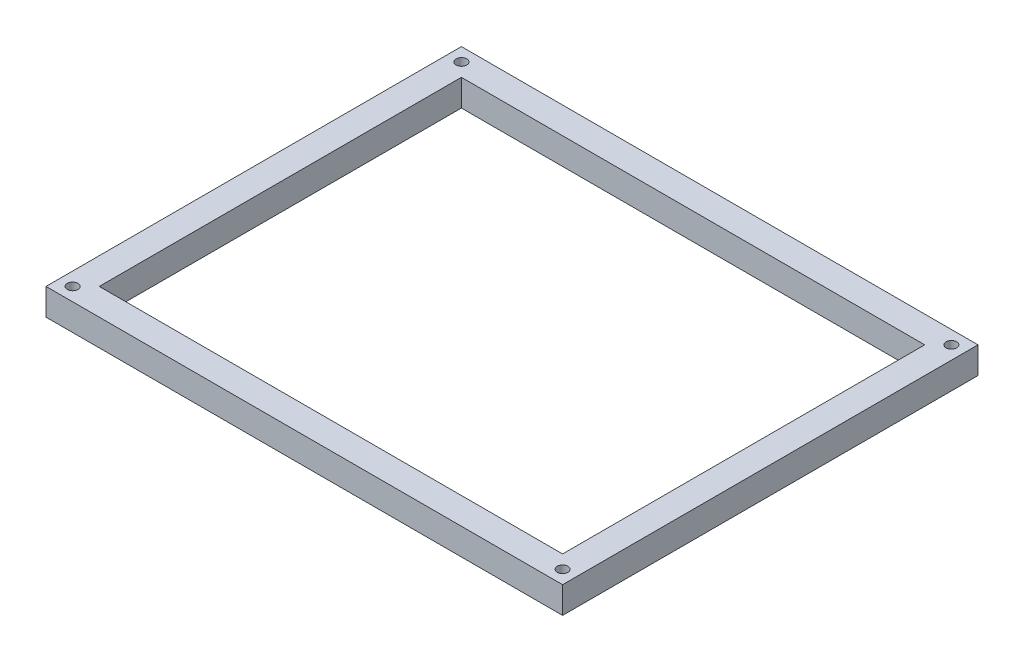
SolidWorks part; units mm, degrees
ref_plane "Front Plane" through (0, 0, 0) normal (0, 0, 1) x (1, 0, 0)
ref_plane "Top Plane" through (0, 0, 0) normal (0, 1, 0) x (1, 0, 0)
ref_plane "Right Plane" through (0, 0, 0) normal (1, 0, 0) x (0, 0, -1)
sketch "Sketch1" plane through (0, 0, 0) normal (0, 1, 0) x (1, 0, 0)
  line L0 (-87, 68) -> (87, 68)
  line L1 (-97, -78) -> (97, -78)
  line L2 (-97, -78) -> (-97, 78)
  line L3 (-97, 78) -> (97, 78)
  line L4 (97, -78) -> (97, 78)
  line L5 (-97, -78) -> (97, 78) construction
  line L6 (-97, 78) -> (97, -78) construction
  line L7 (87, -68) -> (87, 68)
  line L8 (-87, -68) -> (87, -68)
  line L9 (-87, -68) -> (-87, 68)
  point P0 (0, 0)
  dimension "D1" = 10
extrude "Boss-Extrude1" add sketch "Sketch1" along normal blind 10
sketch "Sketch2" plane through (0, 10, 0) normal (0, 1, 0) x (1, 0, 0)
  circle A4 centre (-92, 73) radius 2
  circle A5 centre (-92, -73) radius 2
  circle A6 centre (92, -73) radius 2
  circle A7 centre (92, 73) radius 2
extrude "Cut-Extrude1" cut sketch "Sketch2" against normal blind 10
